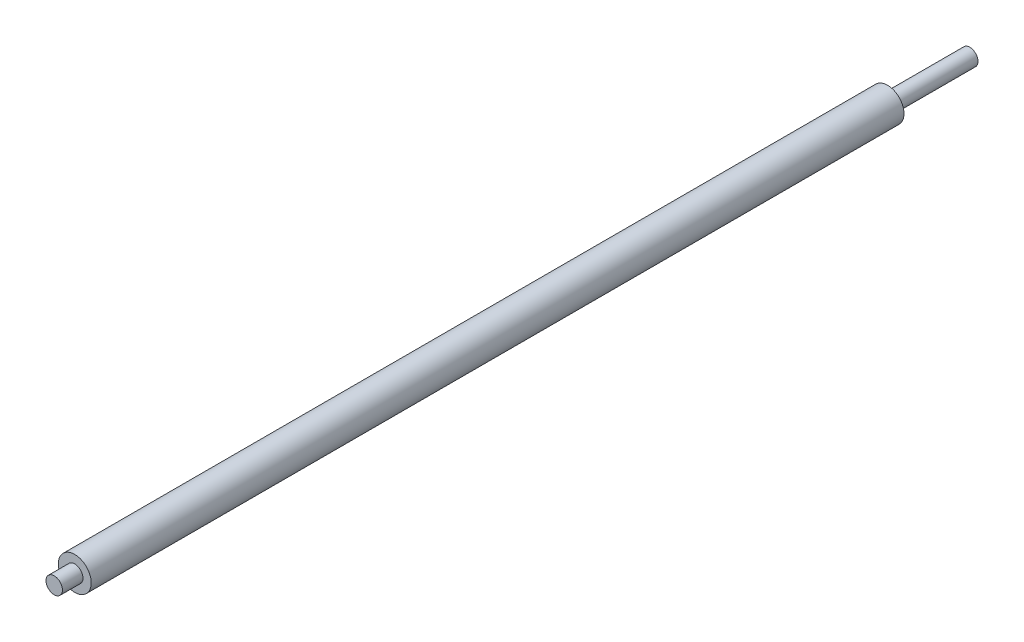
SolidWorks part; units mm, degrees
ref_plane "Front Plane" through (0, 0, 0) normal (0, 0, 1) x (1, 0, 0)
ref_plane "Top Plane" through (0, 0, 0) normal (0, 1, 0) x (1, 0, 0)
ref_plane "Right Plane" through (0, 0, 0) normal (1, 0, 0) x (0, 0, -1)
sketch "Sketch1" plane through (0, 0, 0) normal (0, 0, 1) x (1, 0, 0)
  circle A0 centre (0, 0) radius 6
  dimension "D1" = 12
extrude "Boss-Extrude1" add sketch "Sketch1" along normal mid plane 296.5
sketch "Sketch2" plane through (0, 0, 148.25) normal (0, 0, 1) x (1, 0, 0)
  circle A0 centre (0, 0) radius 3
  dimension "D1" = 6
extrude "Boss-Extrude2" add sketch "Sketch2" along normal blind 7.5
sketch "Sketch3" plane through (0, 0, -148.25) normal (0, 0, -1) x (-1, 0, 0)
  circle A0 centre (0, 0) radius 3
  dimension "D1" = 6
extrude "Boss-Extrude3" add sketch "Sketch3" along normal blind 30
